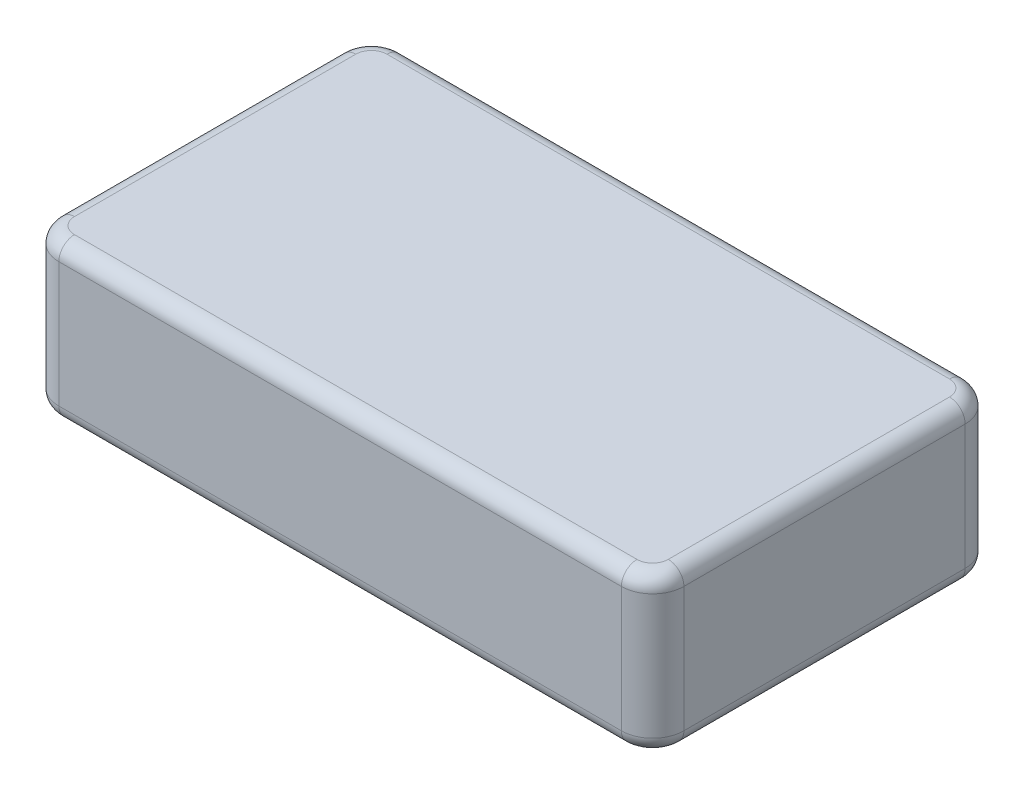
SolidWorks part; units mm, degrees
ref_plane "前视基准面" through (0, 0, 0) normal (0, 0, 1) x (1, 0, 0)
ref_plane "上视基准面" through (0, 0, 0) normal (0, 1, 0) x (1, 0, 0)
ref_plane "右视基准面" through (0, 0, 0) normal (1, 0, 0) x (0, 0, -1)
sketch "草图1" plane through (0, 0, 0) normal (0, 1, 0) x (1, 0, 0)
  line L1 (-20, 11) -> (20, 11)
  line L2 (-20, 11) -> (-20, -11)
  line L3 (-20, -11) -> (20, -11)
  line L4 (20, 11) -> (20, -11)
  line L5 (-20, 11) -> (20, -11) construction
  line L6 (-20, -11) -> (20, 11) construction
  point P0 (0, 0)
  dimension "D1" = 22
  dimension "D2" = 40
extrude "凸台-拉伸1" add sketch "草图1" along normal mid plane 10
fillet "圆角1" radius 2 4 edges at (-20, 0, -11) (20, 0, -11) (20, 0, 11) (-20, 0, 11)
fillet "圆角2" radius 1 16 edges at (-19.4142, -5, 10.4142) (0, -5, 11) (19.4142, -5, 10.4142) (20, -5, 0) (19.4142, -5, -10.4142) (0, -5, -11) (-19.4142, -5, -10.4142) (-20, -5, 0) (19.4142, 5, -10.4142) (20, 5, 0) (19.4142, 5, 10.4142) (0, 5, 11) (-19.4142, 5, 10.4142) (-20, 5, 0) (-19.4142, 5, -10.4142) (0, 5, -11)
sketch "草图2" plane through (0, -5, 0) normal (0, -1, 0) x (1, 0, 0)
  text T0 "1S锂电池" font "汉仪长仿宋体" height 7
extrude "凸台-拉伸2" add sketch "草图2" along normal blind 0.5
